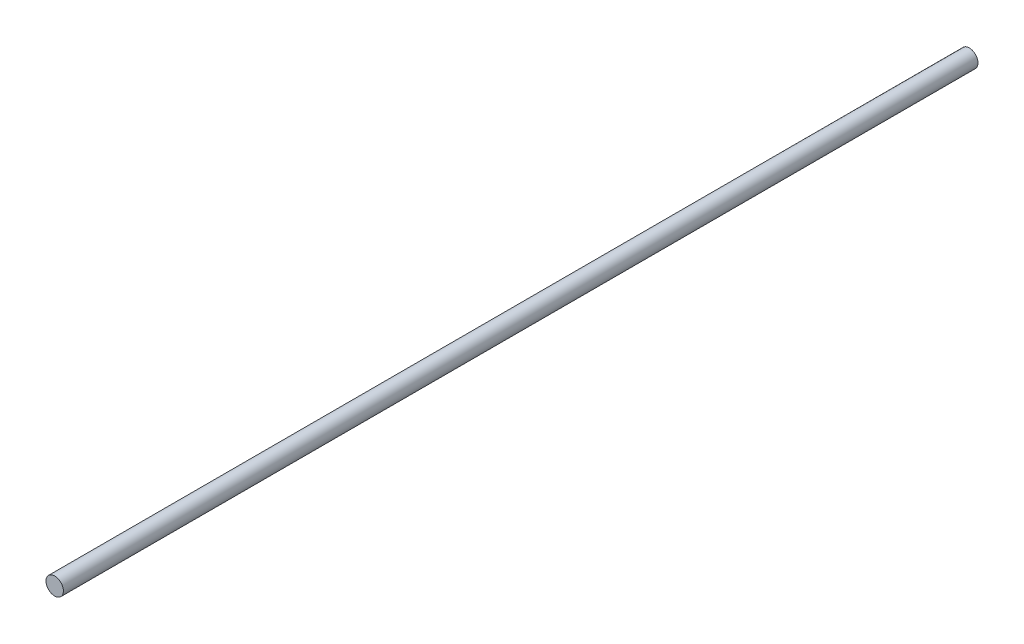
SolidWorks part; units mm, degrees
ref_plane "前视基准面" through (0, 0, 0) normal (0, 0, 1) x (1, 0, 0)
ref_plane "上视基准面" through (0, 0, 0) normal (0, 1, 0) x (1, 0, 0)
ref_plane "右视基准面" through (0, 0, 0) normal (1, 0, 0) x (0, 0, -1)
sketch "草图1" plane through (0, 0, 0) normal (0, 0, 1) x (1, 0, 0)
  circle A0 centre (0, 0) radius 4.7625
  dimension "D1" = 9.525
extrude "凸台-拉伸1" add sketch "草图1" along normal blind 500
